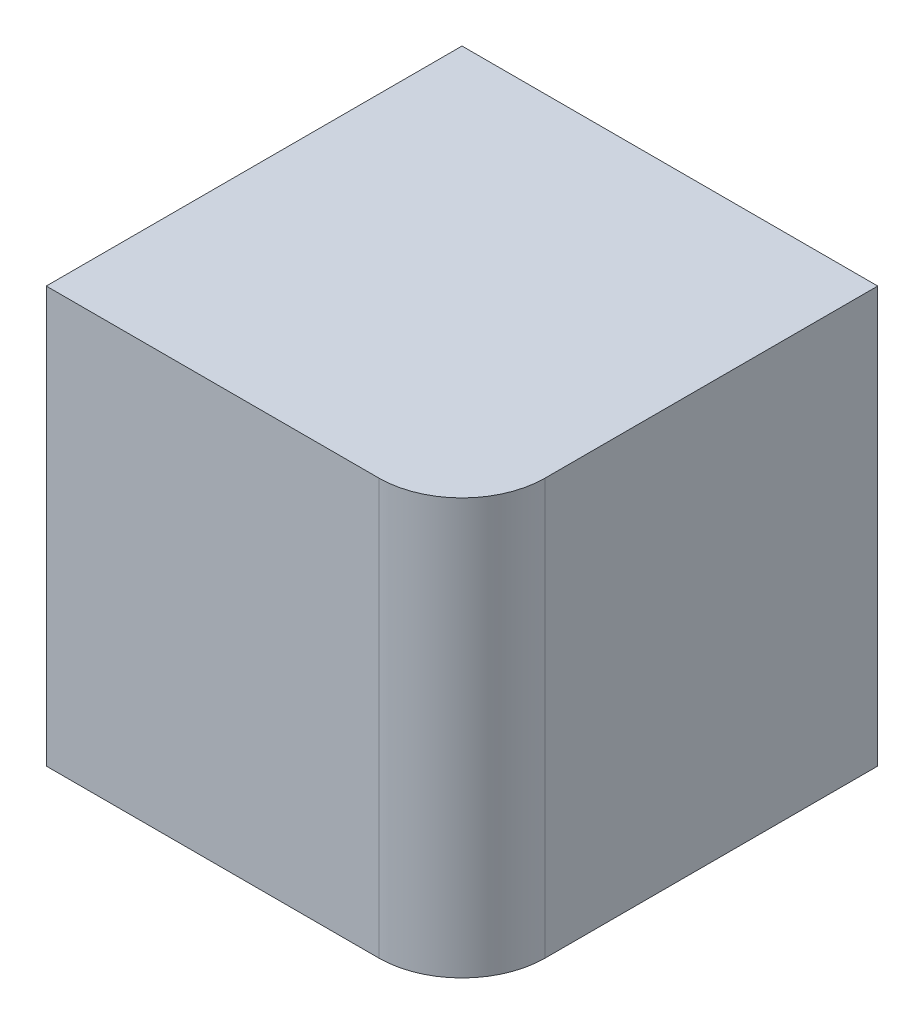
SolidWorks part; units mm, degrees
ref_plane "前视基准面" through (0, 0, 0) normal (0, 0, 1) x (1, 0, 0)
ref_plane "上视基准面" through (0, 0, 0) normal (0, 1, 0) x (1, 0, 0)
ref_plane "右视基准面" through (0, 0, 0) normal (1, 0, 0) x (0, 0, -1)
other "Configuration Table"
sketch "草图1" plane through (0, 0, 0) normal (0, 0, 1) x (1, 0, 0)
  line L1 (0, 0) -> (10, 0)
  line L2 (0, 0) -> (0, 10)
  line L3 (0, 10) -> (10, 10)
  line L4 (10, 0) -> (10, 10)
extrude "凸台-拉伸1" add sketch "草图1" along normal blind 10
fillet "圆角1" radius 2 1 edges at (10, 5, 10)
